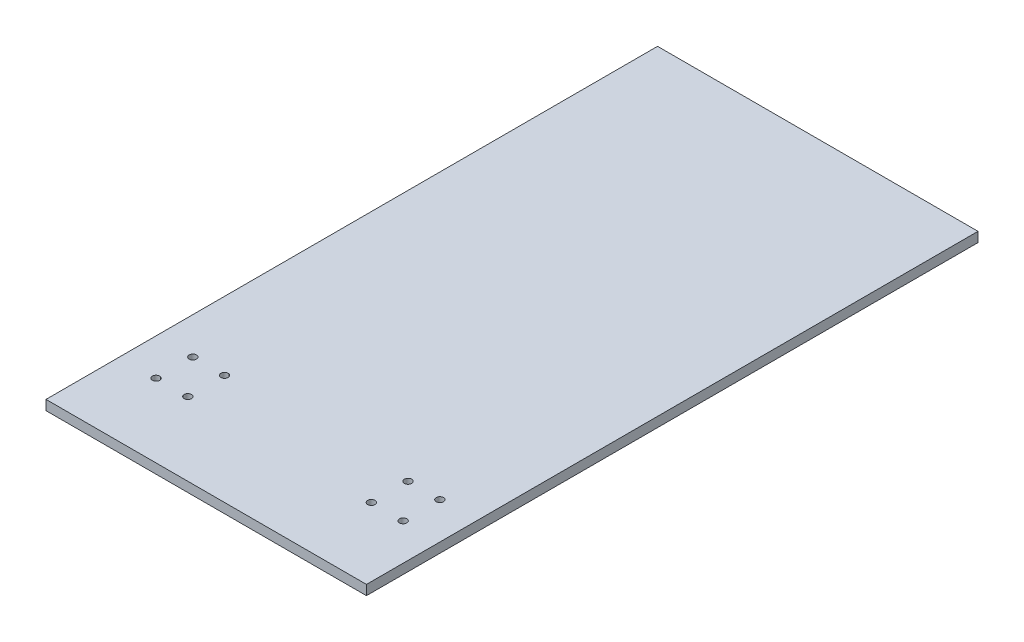
SolidWorks part; units mm, degrees
ref_plane "Front Plane" through (0, 0, 0) normal (0, 0, 1) x (1, 0, 0)
ref_plane "Top Plane" through (0, 0, 0) normal (0, 1, 0) x (1, 0, 0)
ref_plane "Right Plane" through (0, 0, 0) normal (1, 0, 0) x (0, 0, -1)
sketch "Sketch1" plane through (0, 0, 0) normal (0, 1, 0) x (1, 0, 0)
  line L0 (0, 0) -> (0, 125) construction
  line L1 (-65.5, 125) -> (65.5, 125)
  line L2 (-65.5, 125) -> (-65.5, -125)
  line L3 (-65.5, -125) -> (65.5, -125)
  line L4 (65.5, 125) -> (65.5, -125)
  line L5 (0, 0) -> (-65.5, 0) construction
  line L6 (-49, -80) -> (-39, -80) construction
  line L7 (-37.5, -81.5) -> (-37.5, -93.5) construction
  line L8 (-50.5, -81.5) -> (-50.5, -93.5) construction
  line L9 (-49, -95) -> (-39, -95) construction
  circle A0 centre (-50.5, -80) radius 1.5
  circle A1 centre (-37.5, -80) radius 1.5
  circle A2 centre (-37.5, -95) radius 1.5
  circle A3 centre (-50.5, -95) radius 1.5
  circle A4 centre (50.5, -95) radius 1.5
  circle A5 centre (37.5, -95) radius 1.5
  circle A6 centre (37.5, -80) radius 1.5
  circle A7 centre (50.5, -80) radius 1.5
  point P4 (0, 125)
  point P6 (-65.5, 0)
  dimension "D3" = 3
  dimension "D1" = 10
  dimension "D2" = 12
  dimension "D4" = 30
  dimension "D5" = 37.5
  dimension "D6" = 15
  dimension "D7" = 250
extrude "Boss-Extrude1" add sketch "Sketch1" along normal blind 4
